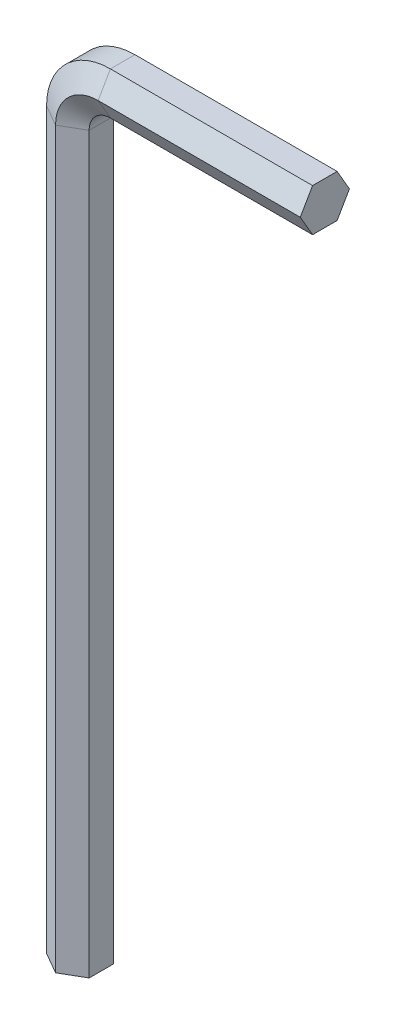
SolidWorks part; units mm, degrees
material "AISI 1020"
ref_plane "Front Plane" through (0, 0, 0) normal (0, 0, 1) x (1, 0, 0)
ref_plane "Top Plane" through (0, 0, 0) normal (0, 1, 0) x (1, 0, 0)
ref_plane "Right Plane" through (0, 0, 0) normal (1, 0, 0) x (0, 0, -1)
sketch "Sketch1" plane through (0, 0, 0) normal (0, 0, 1) x (1, 0, 0)
  line L0 (0, 0) -> (-19, 0)
  line L1 (-25, -6) -> (-25, -75)
  arc A0 (-19, 0) -> (-25, -6) centre (-19, -6) ccw
  dimension "D1" = 6
  dimension "D2" = 75
  dimension "D3" = 25
sketch "Sketch2" plane through (0, 0, 0) normal (1, 0, 0) x (0, 0, -1)
  line L0 (0, 0) -> (0, -6) construction
  line L7 (2.3094, -2) -> (1.1547, 0)
  line L8 (1.1547, 0) -> (-1.1547, 0)
  line L9 (-1.1547, 0) -> (-2.3094, -2)
  line L10 (-2.3094, -2) -> (-1.1547, -4)
  line L11 (-1.1547, -4) -> (1.1547, -4)
  line L12 (1.1547, -4) -> (2.3094, -2)
  circle A0 centre (0, -2) radius 2 construction
  point P11 (0, 0)
  dimension "D1" = 4
sweep "Sweep1" add profiles "Sketch2" path "Sketch1"
